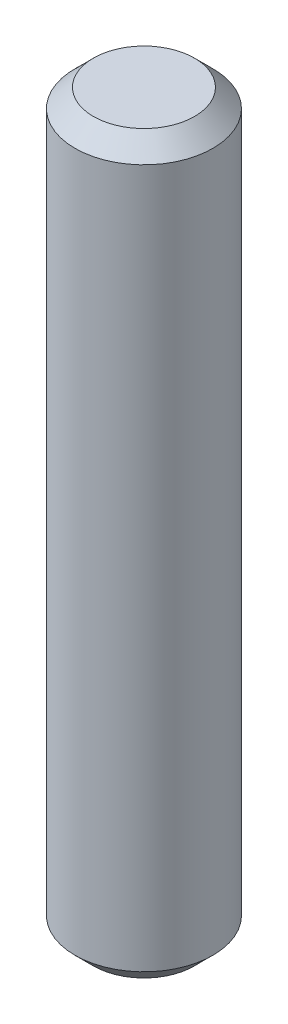
SolidWorks part; units mm, degrees
ref_plane "Front Plane" through (0, 0, 0) normal (0, 0, 1) x (1, 0, 0)
ref_plane "Top Plane" through (0, 0, 0) normal (0, 1, 0) x (1, 0, 0)
ref_plane "Right Plane" through (0, 0, 0) normal (1, 0, 0) x (0, 0, -1)
sketch "Sketch1" plane through (0, 0, 0) normal (0, 1, 0) x (1, 0, 0)
  circle A0 centre (0, 0) radius 0.75
  dimension "D1" = 1.5
extrude "Boss-Extrude1" add sketch "Sketch1" along normal blind 8
chamfer "Chamfer1" distance 0.2 angle 45 2 edges at (0, 0, 0.75) (0, 8, 0.75)
